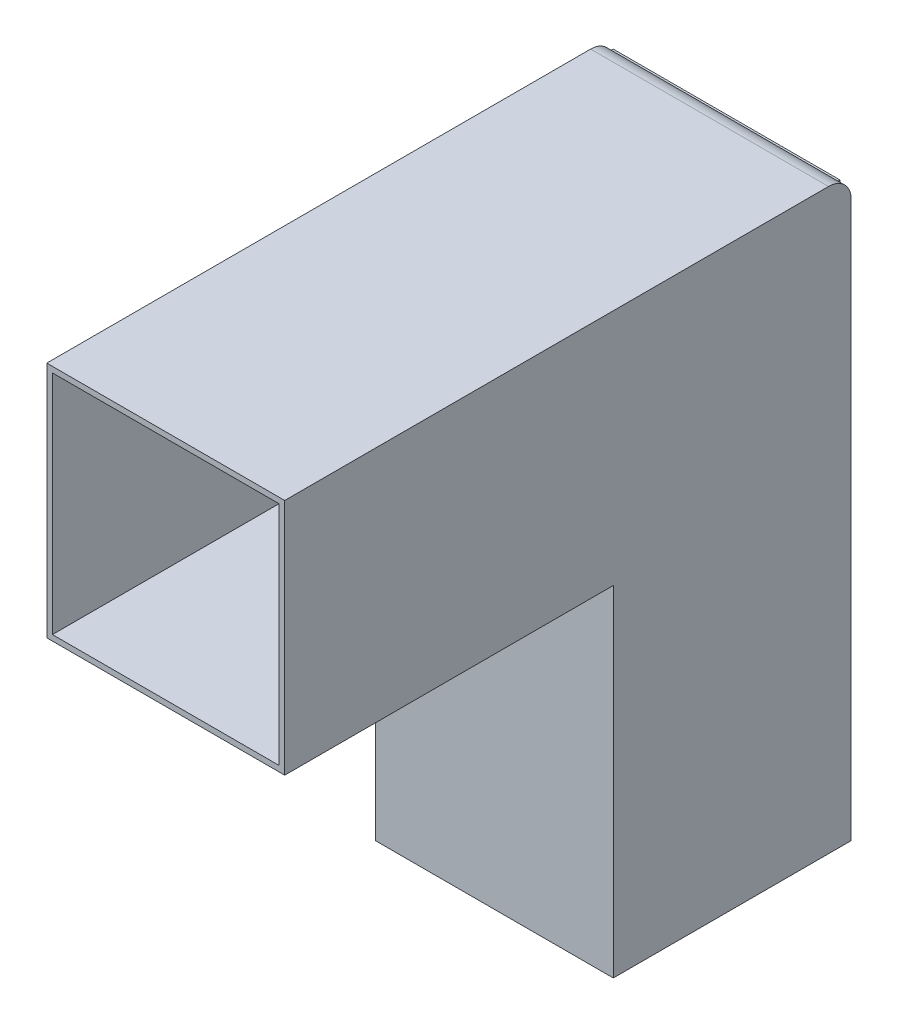
SolidWorks part; units mm, degrees
ref_plane "Plan de face" through (0, 0, 0) normal (0, 0, 1) x (1, 0, 0)
ref_plane "Plan de dessus" through (0, 0, 0) normal (0, 1, 0) x (1, 0, 0)
ref_plane "Plan de droite" through (0, 0, 0) normal (1, 0, 0) x (0, 0, -1)
sketch "Esquisse1" plane through (0, 0, 0) normal (0, 0, 1) x (1, 0, 0)
  line L1 (-10.5, 10.5) -> (10.5, 10.5)
  line L2 (-10.5, 10.5) -> (-10.5, -10.5)
  line L3 (-10.5, -10.5) -> (10.5, -10.5)
  line L4 (10.5, 10.5) -> (10.5, -10.5)
  line L5 (-10.5, 10.5) -> (10.5, -10.5) construction
  line L6 (-10.5, -10.5) -> (10.5, 10.5) construction
  point P0 (0, 0)
  dimension "D1" = 21
  dimension "D2" = 21
extrude "Boss.-Extru.1" add sketch "Esquisse1" along normal blind 50
sketch "Esquisse3" plane through (0, -10.5, 0) normal (0, -1, 0) x (1, 0, 0)
  line L0 (-10.5, 21) -> (10.5, 21)
  line L4 (-10.5, 0) -> (10.5, 0)
  line L5 (10.5, 0) -> (10.5, 50)
  line L6 (10.5, 50) -> (-10.5, 50)
  line L7 (-10.5, 50) -> (-10.5, 0)
  line L8 (-10.5, 0) -> (10.5, 0)
  line L9 (10.5, 0) -> (10.5, 21)
  line L11 (-10.5, 21) -> (-10.5, 0)
  dimension "D2" = 21
  dimension "D1" = 0
extrude "Boss.-Extru.2" add sketch "Esquisse3" along normal blind 30
shell "Coque1" thickness 0.5
fillet "Congé1" radius 2 1 edges at (0, 10.5, 0)
sketch "Esquisse4" plane through (-10.5, 0, 0) normal (-1, 0, 0) x (0, 0, 1)
  circle A0 centre (8, -6.6908) radius 1.5
